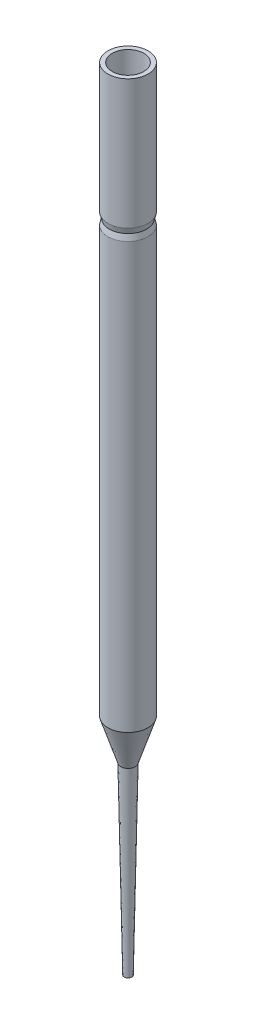
SolidWorks part; units mm, degrees
material "Glas"
ref_plane "Ebene vorne" through (0, 0, 0) normal (0, 0, 1) x (1, 0, 0)
ref_plane "Ebene oben" through (0, 0, 0) normal (0, 1, 0) x (1, 0, 0)
ref_plane "Ebene rechts" through (0, 0, 0) normal (1, 0, 0) x (0, 0, -1)
sketch "Skizze1" plane through (0, 0, 0) normal (0, 0, 1) x (1, 0, 0)
  line L0 (0, 0) -> (0, 12174.4287) construction
  line L1 (0, 0) -> (-13.0934, 0) construction
  line L2 (-2.75, 0) -> (-2.75, -22.5)
  line L3 (-2.75, -22.5) -> (-2.5, -23.5)
  line L4 (-2.5, -23.5) -> (-2.75, -24.5)
  line L5 (-2.75, -24.5) -> (-2.75, -98.5)
  line L6 (-2.75, -98.5) -> (-1, -105.5)
  line L7 (-1, -105.5) -> (-0.4, -137.5)
  line L8 (-0.4, -137.5) -> (-0.65, -137.5)
  line L9 (-5.0661, -22.5) -> (12169.3626, -22.5) construction
  line L10 (-3.75, -23.5) -> (12170.6787, -23.5) construction
  line L11 (-6.2934, -24.5) -> (12168.1354, -24.5) construction
  line L12 (-6.2934, -98.5) -> (12168.1354, -98.5) construction
  line L13 (-9.5711, -105.5) -> (12164.8576, -105.5) construction
  line L14 (-3.8878, -137.5) -> (12170.5409, -137.5) construction
  line L15 (-2.75, 0) -> (-3.5, 0)
  line L16 (-3.5, 0) -> (-3.5, -22.5)
  line L17 (-3.5, -22.5) -> (-3.25, -23.5)
  line L18 (-3.25, -23.5) -> (-3.5, -24.5)
  line L19 (-3.5, -24.5) -> (-3.5, -98.5)
  line L20 (-3.5, -98.5) -> (-1.25, -105.5)
  line L21 (-1.25, -105.5) -> (-0.65, -137.5)
  dimension "D1" = 32
  dimension "D2" = 137.5
  dimension "D3" = 74
  dimension "D4" = 1
  dimension "D5" = 1
  dimension "D6" = 22.5
  dimension "D7" = 5.5
  dimension "D8" = 5.5
  dimension "D9" = 7
  dimension "D10" = 7
  dimension "D11" = 5
  dimension "D12" = 6.5
  dimension "D13" = 2
  dimension "D14" = 2.5
  dimension "D15" = 0.8
  dimension "D16" = 1.3
revolve "Rotation1" add sketch "Skizze1" angle 360 about L0
